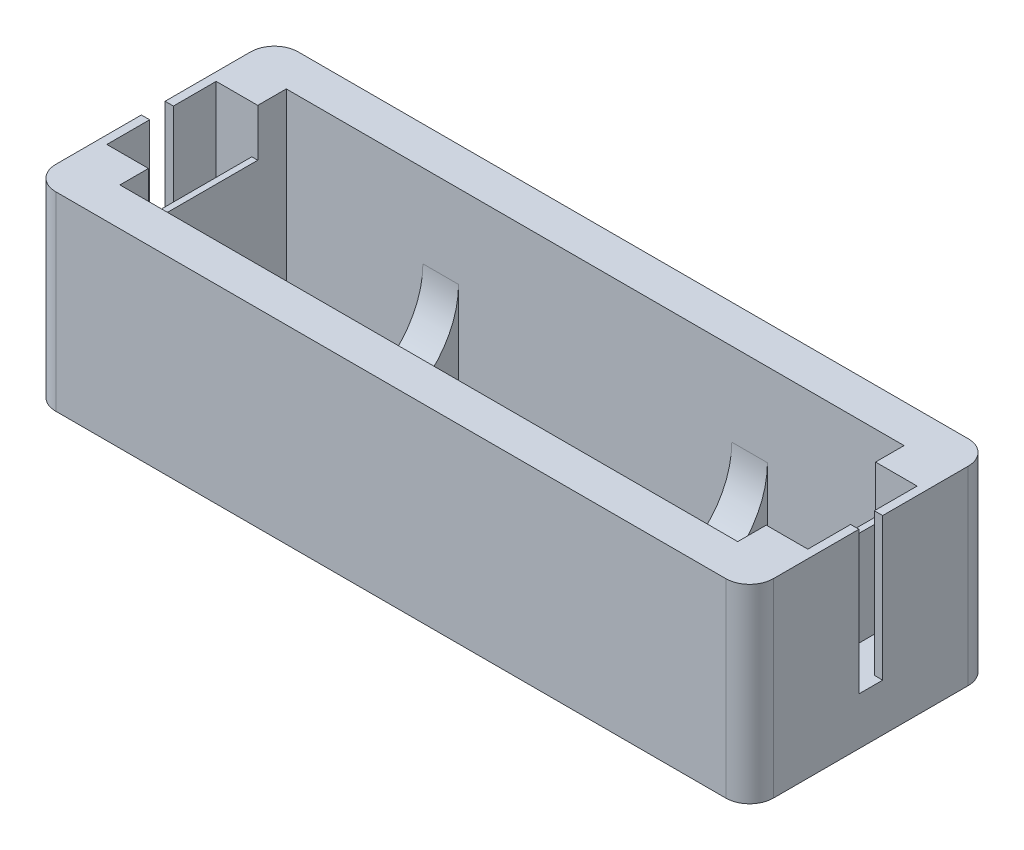
SolidWorks part; units mm, degrees
ref_plane "Front Plane" through (0, 0, 0) normal (0, 0, 1) x (1, 0, 0)
ref_plane "Top Plane" through (0, 0, 0) normal (0, 1, 0) x (1, 0, 0)
ref_plane "Right Plane" through (0, 0, 0) normal (1, 0, 0) x (0, 0, -1)
sketch "Sketch2" plane through (0, 0, 0) normal (0, 1, 0) x (1, 0, 0)
  line L1 (-30.2, -10.2) -> (30.2, -10.2)
  line L2 (-30.2, -10.2) -> (-30.2, 10.2)
  line L3 (-30.2, 10.2) -> (30.2, 10.2)
  line L4 (30.2, -10.2) -> (30.2, 10.2)
  line L5 (-30.2, -10.2) -> (30.2, 10.2) construction
  line L6 (-30.2, 10.2) -> (30.2, -10.2) construction
  point P0 (0, 0)
  dimension "D1" = 60.4
  dimension "D2" = 20.4
extrude "Boss-Extrude1" add sketch "Sketch2" along normal blind 16
sketch "Sketch3" plane through (0, 16, 0) normal (0, 1, 0) x (1, 0, 0)
  line L0 (30.2, -10.2) -> (30.2, 10.2) construction
  line L1 (-26, 7) -> (26, 7)
  line L2 (-26, 7) -> (-26, -7)
  line L3 (-26, -7) -> (26, -7)
  line L4 (26, 7) -> (26, -7)
  line L5 (-26, 7) -> (26, -7) construction
  line L6 (-26, -7) -> (26, 7) construction
  line L7 (-30.2, -10.2) -> (30.2, -10.2) construction
  point P0 (0, 0)
  dimension "D1" = 4.2
  dimension "D2" = 3.2
extrude "Cut-Extrude1" cut sketch "Sketch3" against normal offset from surface (14 mm away) 2 up to face at (0, 0, 0)
fillet "Fillet1" radius 2 4 edges at (-30.2, 8, -10.2) (30.2, 8, -10.2) (30.2, 8, 10.2) (-30.2, 8, 10.2)
sketch "Sketch4" plane through (0, 16, 0) normal (0, 1, 0) x (1, 0, 0)
  line L0 (-26, 7) -> (-26, -7) construction
  line L1 (-26, 0) -> (-26.5, 0)
  line L2 (-26, 0) -> (-26, 4.6)
  line L3 (-26, 4.6) -> (-26.5, 4.6)
  line L4 (-26.5, 0) -> (-26.5, 4.6)
  dimension "D1" = 0.5
  dimension "D2" = 4.6
extrude "Cut-Extrude2" cut sketch "Sketch4" against normal offset from surface (4 mm away) 4 up to face at (0, 16, 0)
sketch "Sketch5" plane through (0, 16, 0) normal (0, 1, 0) x (1, 0, 0)
  line L1 (-26.5, 0) -> (-29.5, 0)
  line L2 (-26.5, 0) -> (-26.5, 4.6)
  line L3 (-26.5, 4.6) -> (-29.5, 4.6)
  line L4 (-29.5, 0) -> (-29.5, 4.6)
  dimension "D2" = 4.6
  dimension "D1" = 3
extrude "Cut-Extrude3" cut sketch "Sketch5" against normal offset from surface (12 mm away) 12 up to face at (-13.125, 16, -1.15)
mirror "Mirror4" about plane through (0, 0, 0) normal (1, 0, 0) of "Cut-Extrude3", "Cut-Extrude2"
mirror "Mirror5" about plane through (0, 0, 0) normal (0, 0, 1) of "Mirror4", "Cut-Extrude3"
sketch "Sketch6" plane through (30.2, 0, 0) normal (1, 0, 0) x (0, 0, -1)
  line L0 (-8.2, 0) -> (8.2, 0) construction
  circle A0 centre (0, 12) radius 0.75
  dimension "D1" = 1.5
  dimension "D2" = 12
ref_plane "Plane1" through (-13, 0, 0) normal (1, 0, 0) x (0, 0, -1)
sketch "Sketch7" plane through (-13, 0, 0) normal (1, 0, 0) x (0, 0, -1)
  line L0 (-7, 2) -> (7, 2) construction
  line L1 (7, 2) -> (7, 16) construction
  line L3 (-7, 2) -> (-7, 16) construction
  circle A0 centre (0, 9) radius 7
sketch "Sketch8" plane through (0, 2, 0) normal (0, 1, 0) x (1, 0, 0)
  line L0 (-13, -7) -> (-13, 7) construction
  line L1 (-14.5, -7) -> (-11.5, -7)
  line L2 (-14.5, -7) -> (-14.5, 7)
  line L3 (-14.5, 7) -> (-11.5, 7)
  line L4 (-11.5, -7) -> (-11.5, 7)
  line L5 (-14.5, -7) -> (-11.5, 7) construction
  line L6 (-14.5, 7) -> (-11.5, -7) construction
  line L7 (26, 7) -> (-26, 7) construction
  point P0 (-13, 0)
  dimension "D1" = 3
extrude "Boss-Extrude2" add sketch "Sketch8" along normal blind 7
extrude "Cut-Extrude5" cut sketch "Sketch7" against normal up to next and the other way up to next contours A0
mirror "Mirror7" about plane through (0, 0, 0) normal (1, 0, 0) of "Cut-Extrude5", "Boss-Extrude2"
sketch "Sketch9" plane through (0, 16, 0) normal (0, 1, 0) x (1, 0, 0)
  line L0 (-29.5, 4.6) -> (-29.5, -4.6) construction
  line L1 (-29.5, 0) -> (-30.2, 0)
  line L2 (-29.5, 0) -> (-29.5, 1)
  line L3 (-29.5, 1) -> (-30.2, 1)
  line L4 (-30.2, 0) -> (-30.2, 1)
  line L5 (-30.2, 8.2) -> (-30.2, -8.2) construction
  dimension "D1" = 1
extrude "Cut-Extrude6" cut sketch "Sketch9" against normal up to surface (12 mm away) up to face at (-28, 4, 0)
mirror "Mirror8" about plane through (0, 0, 0) normal (0, 0, 1) of "Cut-Extrude6" second plane through (0, 0, 0) second plane normal (1, 0, 0)
equation "\"D1@Sketch2\"=44 + 6.4 + 10"
equation "\"D2@Sketch2\" = 10 + 6.4 + 4"
equation "\"D1@Boss-Extrude1\" = 10 + 2 + 4"
equation "\"D1@Sketch3\"=4.2"
equation "\"D2@Sketch3\"=3.2"
equation "\"D1@Cut-Extrude1\"=2"
equation "\"D1@Fillet1\"=2"
equation "\"D2@Sketch4\"=4.6"
equation "\"D1@Sketch5\"=3"
equation "\"D2@Sketch5\"=4.6"
equation "\"D1@Sketch8\"=3"
equation "\"D2@Sketch6\"=12"
equation "\"D1@Sketch9\"=1"
